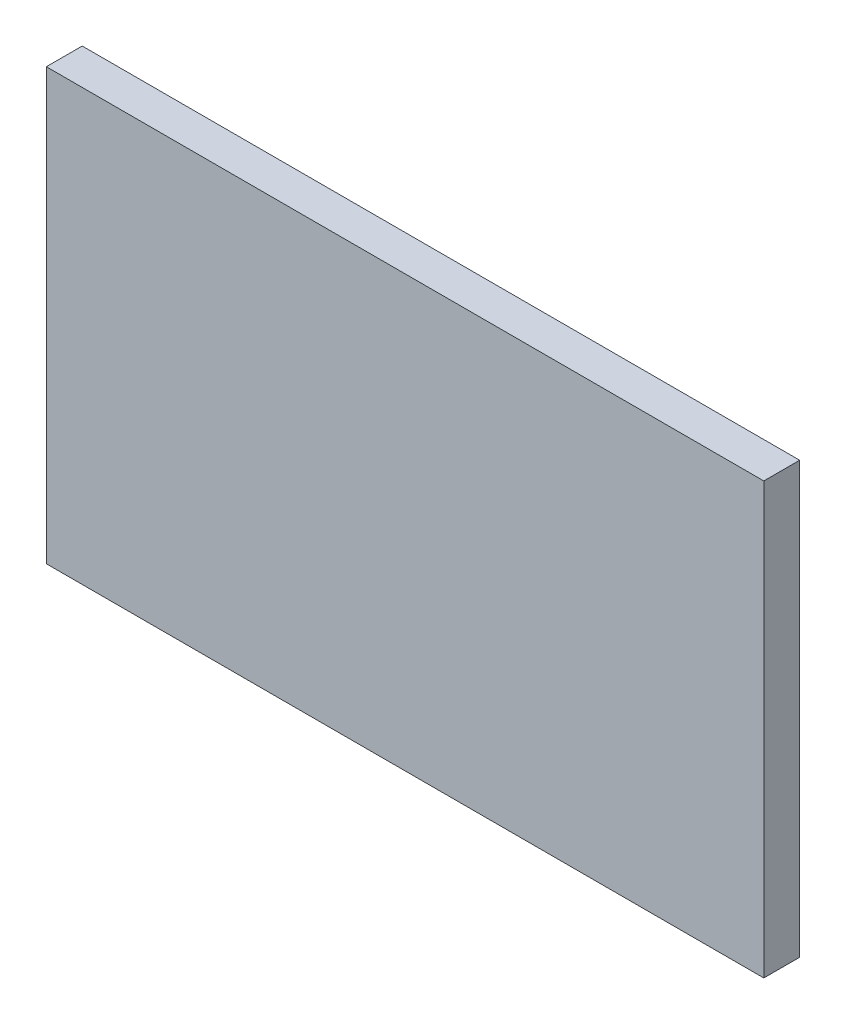
SolidWorks part; units mm, degrees
ref_plane "Спереди" through (0, 0, 0) normal (0, 0, 1) x (1, 0, 0)
ref_plane "Сверху" through (0, 0, 0) normal (0, 1, 0) x (1, 0, 0)
ref_plane "Справа" through (0, 0, 0) normal (1, 0, 0) x (0, 0, -1)
sketch "Эскиз1" plane through (0, 0, 0) normal (0, 0, 1) x (1, 0, 0)
  line L1 (-100, -60) -> (100, -60)
  line L2 (-100, -60) -> (-100, 60)
  line L3 (-100, 60) -> (100, 60)
  line L4 (100, -60) -> (100, 60)
extrude "Бобышка-Вытянуть1" add sketch "Эскиз1" along normal blind 10
